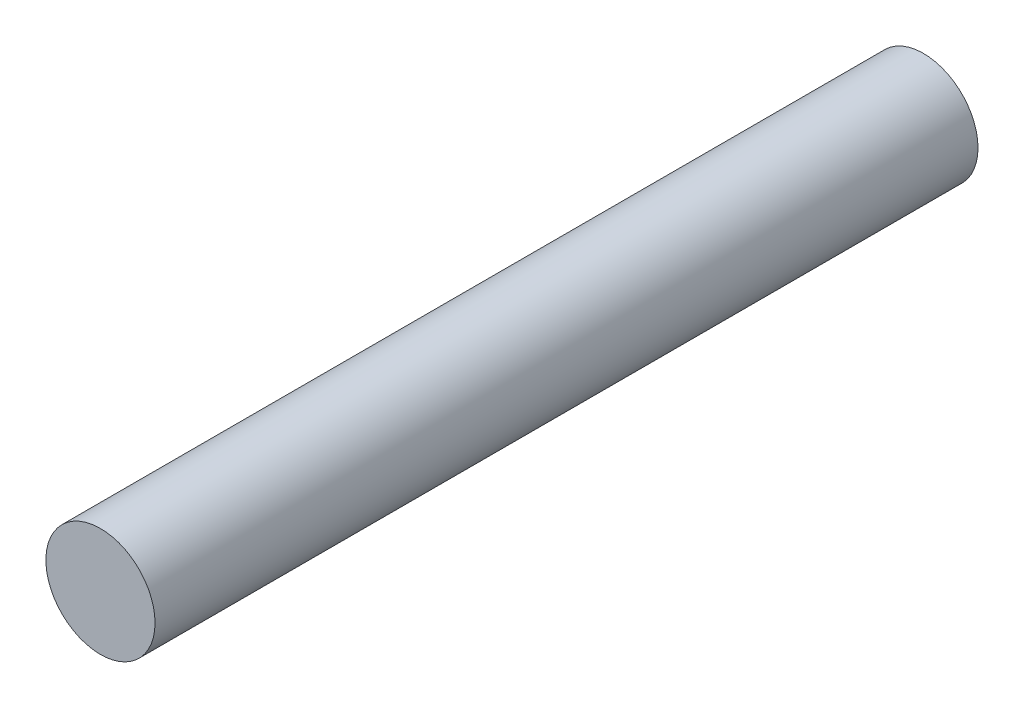
SolidWorks part; units mm, degrees
ref_plane "Alzado" through (0, 0, 0) normal (0, 0, 1) x (1, 0, 0)
ref_plane "Planta" through (0, 0, 0) normal (0, 1, 0) x (1, 0, 0)
ref_plane "Vista lateral" through (0, 0, 0) normal (1, 0, 0) x (0, 0, -1)
sketch "Croquis1" plane through (0, 0, 0) normal (0, 0, 1) x (1, 0, 0)
  circle A0 centre (0, 0) radius 4
  dimension "D1" = 8
extrude "Saliente-Extruir1" add sketch "Croquis1" along normal blind 60.325
